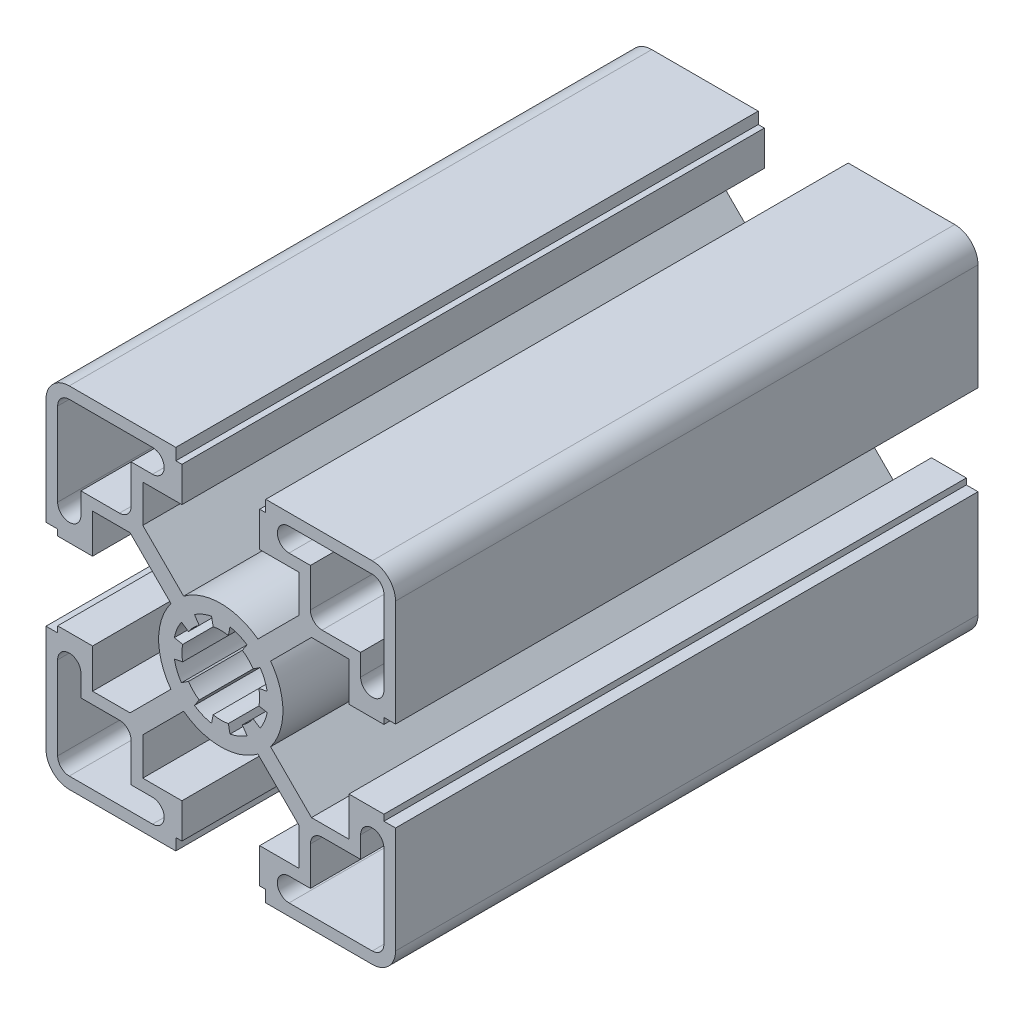
SolidWorks part; units mm, degrees
ref_plane "Front Plane" through (0, 0, 0) normal (0, 0, 1) x (1, 0, 0)
ref_plane "Top Plane" through (0, 0, 0) normal (0, 1, 0) x (1, 0, 0)
ref_plane "Right Plane" through (0, 0, 0) normal (1, 0, 0) x (0, 0, -1)
sketch "Sketch1" plane through (0, 0, 0) normal (0, 0, 1) x (1, 0, 0)
  line L2 (-19.5072, 22.5044) -> (-5.7912, 22.5044)
  line L3 (-5.7912, 22.5044) -> (-5.7912, 21.0058)
  line L4 (-5.7912, 21.0058) -> (-5.0038, 21.0058)
  line L6 (-5.0038, 21.0058) -> (-5.0038, 16.51)
  line L7 (-5.0038, 16.51) -> (-10.0457, 16.51)
  line L8 (-10.0457, 16.51) -> (-10.0457, 11.6801)
  line L9 (-10.0457, 11.6801) -> (-4.781, 6.4154)
  line L11 (-11.6801, 10.0457) -> (-6.4154, 4.781)
  line L12 (-16.51, 10.0457) -> (-11.6801, 10.0457)
  line L13 (-16.51, 5.0038) -> (-16.51, 10.0457)
  line L14 (-21.0058, 5.0038) -> (-16.51, 5.0038)
  line L15 (-21.0058, 5.7912) -> (-21.0058, 5.0038)
  line L16 (-22.5044, 5.7912) -> (-21.0058, 5.7912)
  line L17 (-22.5044, 19.5072) -> (-22.5044, 5.7912)
  line L18 (-18.0086, 11.5443) -> (-13.0429, 11.5443)
  line L19 (-18.0086, 11.5443) -> (-18.0086, 8.7884)
  line L20 (-11.5443, 18.0086) -> (-11.5443, 13.0429)
  line L21 (-21.0058, 19.5072) -> (-21.0058, 8.7884)
  line L23 (-11.5443, 18.0086) -> (-8.7884, 18.0086)
  line L24 (-19.5072, 21.0058) -> (-8.7884, 21.0058)
  line L25 (1.1893, 5.9789) -> (0.9762, 4.9077)
  line L26 (-1.1893, 5.9789) -> (-0.9762, 4.9077)
  line L27 (5.0686, 3.3868) -> (4.1605, 2.78)
  line L28 (3.3868, 5.0686) -> (2.78, 4.1605)
  line L29 (5.9789, -1.1893) -> (4.9077, -0.9762)
  line L30 (5.9789, 1.1893) -> (4.9077, 0.9762)
  line L31 (3.3868, -5.0686) -> (2.78, -4.1605)
  line L32 (5.0686, -3.3868) -> (4.1605, -2.78)
  line L33 (-1.1893, -5.9789) -> (-0.9762, -4.9077)
  line L34 (1.1893, -5.9789) -> (0.9762, -4.9077)
  line L35 (-5.0686, -3.3868) -> (-4.1605, -2.78)
  line L36 (-3.3868, -5.0686) -> (-2.78, -4.1605)
  line L37 (-5.9789, 1.1893) -> (-4.9077, 0.9762)
  line L38 (-5.9789, -1.1893) -> (-4.9077, -0.9762)
  line L39 (-3.3868, 5.0686) -> (-2.78, 4.1605)
  line L40 (-5.0686, 3.3868) -> (-4.1605, 2.78)
  line L41 (11.5443, 18.0086) -> (8.7884, 18.0086)
  line L42 (19.5072, 21.0058) -> (8.7884, 21.0058)
  line L43 (19.5072, 22.5044) -> (5.7912, 22.5044)
  line L44 (5.7912, 22.5044) -> (5.7912, 21.0058)
  line L45 (5.7912, 21.0058) -> (5.0038, 21.0058)
  line L46 (5.0038, 21.0058) -> (5.0038, 16.51)
  line L47 (5.0038, 16.51) -> (10.0457, 16.51)
  line L48 (10.0457, 16.51) -> (10.0457, 11.6801)
  line L49 (10.0457, 11.6801) -> (4.781, 6.4154)
  line L50 (11.6801, 10.0457) -> (6.4154, 4.781)
  line L51 (21.0058, 19.5072) -> (21.0058, 8.7884)
  line L52 (11.5443, 18.0086) -> (11.5443, 13.0429)
  line L53 (18.0086, 11.5443) -> (18.0086, 8.7884)
  line L54 (18.0086, 11.5443) -> (13.0429, 11.5443)
  line L55 (22.5044, 19.5072) -> (22.5044, 5.7912)
  line L56 (22.5044, 5.7912) -> (21.0058, 5.7912)
  line L57 (21.0058, 5.7912) -> (21.0058, 5.0038)
  line L58 (21.0058, 5.0038) -> (16.51, 5.0038)
  line L59 (16.51, 5.0038) -> (16.51, 10.0457)
  line L60 (16.51, 10.0457) -> (11.6801, 10.0457)
  line L61 (16.51, -10.0457) -> (11.6801, -10.0457)
  line L62 (16.51, -5.0038) -> (16.51, -10.0457)
  line L63 (21.0058, -5.0038) -> (16.51, -5.0038)
  line L64 (21.0058, -5.7912) -> (21.0058, -5.0038)
  line L65 (22.5044, -5.7912) -> (21.0058, -5.7912)
  line L66 (22.5044, -19.5072) -> (22.5044, -5.7912)
  line L67 (18.0086, -11.5443) -> (13.0429, -11.5443)
  line L68 (18.0086, -11.5443) -> (18.0086, -8.7884)
  line L69 (11.5443, -18.0086) -> (11.5443, -13.0429)
  line L70 (21.0058, -19.5072) -> (21.0058, -8.7884)
  line L71 (11.6801, -10.0457) -> (6.4154, -4.781)
  line L72 (10.0457, -11.6801) -> (4.781, -6.4154)
  line L73 (10.0457, -16.51) -> (10.0457, -11.6801)
  line L74 (5.0038, -16.51) -> (10.0457, -16.51)
  line L75 (5.0038, -21.0058) -> (5.0038, -16.51)
  line L76 (5.7912, -21.0058) -> (5.0038, -21.0058)
  line L77 (5.7912, -22.5044) -> (5.7912, -21.0058)
  line L78 (19.5072, -22.5044) -> (5.7912, -22.5044)
  line L79 (19.5072, -21.0058) -> (8.7884, -21.0058)
  line L80 (11.5443, -18.0086) -> (8.7884, -18.0086)
  line L81 (-11.5443, -18.0086) -> (-8.7884, -18.0086)
  line L82 (-19.5072, -21.0058) -> (-8.7884, -21.0058)
  line L83 (-19.5072, -22.5044) -> (-5.7912, -22.5044)
  line L84 (-5.7912, -22.5044) -> (-5.7912, -21.0058)
  line L85 (-5.7912, -21.0058) -> (-5.0038, -21.0058)
  line L86 (-5.0038, -21.0058) -> (-5.0038, -16.51)
  line L87 (-5.0038, -16.51) -> (-10.0457, -16.51)
  line L88 (-10.0457, -16.51) -> (-10.0457, -11.6801)
  line L89 (-10.0457, -11.6801) -> (-4.781, -6.4154)
  line L90 (-11.6801, -10.0457) -> (-6.4154, -4.781)
  line L91 (-21.0058, -19.5072) -> (-21.0058, -8.7884)
  line L92 (-11.5443, -18.0086) -> (-11.5443, -13.0429)
  line L93 (-18.0086, -11.5443) -> (-18.0086, -8.7884)
  line L94 (-18.0086, -11.5443) -> (-13.0429, -11.5443)
  line L95 (-22.5044, -19.5072) -> (-22.5044, -5.7912)
  line L96 (-22.5044, -5.7912) -> (-21.0058, -5.7912)
  line L97 (-21.0058, -5.7912) -> (-21.0058, -5.0038)
  line L98 (-21.0058, -5.0038) -> (-16.51, -5.0038)
  line L99 (-16.51, -5.0038) -> (-16.51, -10.0457)
  line L100 (-16.51, -10.0457) -> (-11.6801, -10.0457)
  arc A0 (-22.5044, 19.5072) -> (-19.5072, 22.5044) centre (-19.5072, 19.5072) cw
  arc A1 (-21.0058, 8.7884) -> (-18.0086, 8.7884) centre (-19.5072, 8.7884) ccw
  arc A2 (-21.0058, 19.5072) -> (-19.5072, 21.0058) centre (-19.5072, 19.5072) cw
  arc A3 (-8.7884, 21.0058) -> (-8.7884, 18.0086) centre (-8.7884, 19.5072) cw
  arc A4 (-11.5443, 13.0429) -> (-13.0429, 11.5443) centre (-13.0429, 13.0429) cw
  arc A5 (6.4154, -4.781) -> (6.4154, 4.781) centre (0, 0) ccw
  arc A6 (0.9762, 4.9077) -> (-0.9762, 4.9077) centre (0, 0) ccw
  arc A7 (-5.0686, 3.3868) -> (-5.9789, 1.1893) centre (0, 0) ccw
  arc A8 (4.1605, 2.78) -> (2.78, 4.1605) centre (0, 0) ccw
  arc A9 (4.9077, -0.9762) -> (4.9077, 0.9762) centre (0, 0) ccw
  arc A10 (2.78, -4.1605) -> (4.1605, -2.78) centre (0, 0) ccw
  arc A11 (-0.9762, -4.9077) -> (0.9762, -4.9077) centre (0, 0) ccw
  arc A12 (-4.1605, -2.78) -> (-2.78, -4.1605) centre (0, 0) ccw
  arc A13 (-4.9077, 0.9762) -> (-4.9077, -0.9762) centre (0, 0) ccw
  arc A14 (-2.78, 4.1605) -> (-4.1605, 2.78) centre (0, 0) ccw
  arc A15 (-5.9789, -1.1893) -> (-5.0686, -3.3868) centre (0, 0) ccw
  arc A16 (-3.3868, -5.0686) -> (-1.1893, -5.9789) centre (0, 0) ccw
  arc A17 (1.1893, -5.9789) -> (3.3868, -5.0686) centre (0, 0) ccw
  arc A18 (5.0686, -3.3868) -> (5.9789, -1.1893) centre (0, 0) ccw
  arc A19 (5.9789, 1.1893) -> (5.0686, 3.3868) centre (0, 0) ccw
  arc A20 (3.3868, 5.0686) -> (1.1893, 5.9789) centre (0, 0) ccw
  arc A21 (-1.1893, 5.9789) -> (-3.3868, 5.0686) centre (0, 0) ccw
  arc A22 (8.7884, 21.0058) -> (8.7884, 18.0086) centre (8.7884, 19.5072) ccw
  arc A23 (21.0058, 19.5072) -> (19.5072, 21.0058) centre (19.5072, 19.5072) ccw
  arc A24 (22.5044, 19.5072) -> (19.5072, 22.5044) centre (19.5072, 19.5072) ccw
  arc A25 (11.5443, 13.0429) -> (13.0429, 11.5443) centre (13.0429, 13.0429) ccw
  arc A26 (21.0058, 8.7884) -> (18.0086, 8.7884) centre (19.5072, 8.7884) cw
  arc A27 (21.0058, -8.7884) -> (18.0086, -8.7884) centre (19.5072, -8.7884) ccw
  arc A28 (11.5443, -13.0429) -> (13.0429, -11.5443) centre (13.0429, -13.0429) cw
  arc A29 (22.5044, -19.5072) -> (19.5072, -22.5044) centre (19.5072, -19.5072) cw
  arc A30 (21.0058, -19.5072) -> (19.5072, -21.0058) centre (19.5072, -19.5072) cw
  arc A31 (8.7884, -21.0058) -> (8.7884, -18.0086) centre (8.7884, -19.5072) cw
  arc A32 (-8.7884, -21.0058) -> (-8.7884, -18.0086) centre (-8.7884, -19.5072) ccw
  arc A33 (-21.0058, -19.5072) -> (-19.5072, -21.0058) centre (-19.5072, -19.5072) ccw
  arc A34 (-22.5044, -19.5072) -> (-19.5072, -22.5044) centre (-19.5072, -19.5072) ccw
  arc A35 (-11.5443, -13.0429) -> (-13.0429, -11.5443) centre (-13.0429, -13.0429) ccw
  arc A36 (-21.0058, -8.7884) -> (-18.0086, -8.7884) centre (-19.5072, -8.7884) cw
  arc A37 (4.781, 6.4154) -> (-4.781, 6.4154) centre (0, 0) ccw
  arc A38 (-4.781, -6.4154) -> (4.781, -6.4154) centre (0, 0) ccw
  arc A39 (-6.4154, 4.781) -> (-6.4154, -4.781) centre (0, 0) ccw
extrude "Boss-Extrude1" add sketch "Sketch1" along normal mid plane 75
